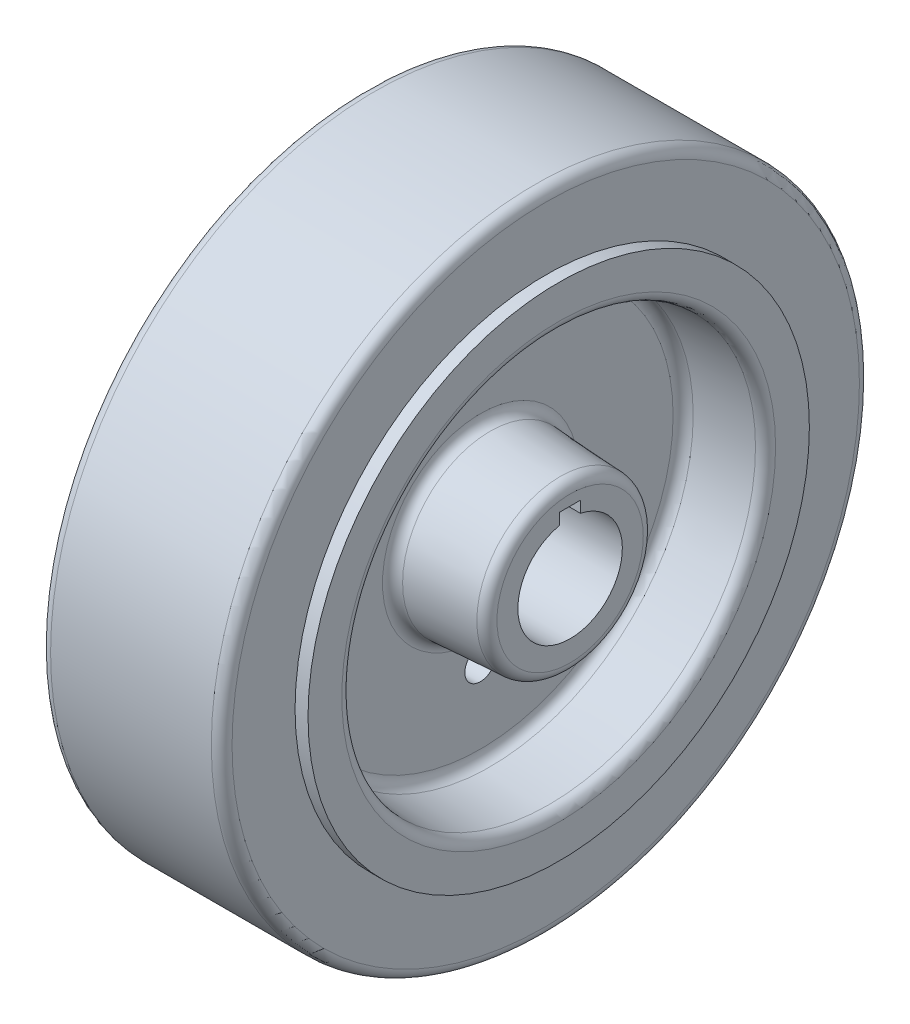
SolidWorks part; units mm, degrees
ref_plane "Front Plane" through (0, 0, 0) normal (0, 0, 1) x (1, 0, 0)
ref_plane "Top Plane" through (0, 0, 0) normal (0, 1, 0) x (1, 0, 0)
ref_plane "Right Plane" through (0, 0, 0) normal (1, 0, 0) x (0, 0, -1)
sketch "Sketch1" plane through (0, 0, 0) normal (0, 0, 1) x (1, 0, 0)
  line L0 (-17.5, -62.5) -> (17.5, -62.5)
  line L1 (-17.5, -62.5) -> (-17.5, -48.35)
  line L2 (20, -39.95) -> (4.9, -39.05)
  line L3 (4.9, -39.05) -> (4.9, -17)
  line L4 (4.9, -17) -> (22.2, -16)
  line L5 (22.2, -16) -> (22.2, -10.075)
  line L6 (0, -62.5) -> (0, 0) construction
  line L7 (0, 0) -> (22.2, 0) construction
  line L8 (22.2, -10.075) -> (-22.2, -10.075)
  line L9 (-22.2, -16) -> (-22.2, -10.075)
  line L10 (-4.9, -17) -> (-22.2, -16)
  line L11 (-4.9, -39.05) -> (-4.9, -17)
  line L12 (-20, -39.95) -> (-4.9, -39.05)
  line L13 (-17.5, -48.35) -> (-20, -48.35)
  line L14 (17.5, -62.5) -> (17.5, -48.35)
  line L15 (17.5, -48.35) -> (20, -48.35)
  line L16 (20, -48.35) -> (20, -39.95)
  line L17 (-20, -48.35) -> (-20, -39.95)
  point P12 (0, -10.075)
  dimension "D1" = 44.4
  dimension "D2" = 35
  dimension "D3" = 20.15
  dimension "D4" = 32
  dimension "D5" = 125
  dimension "D6" = 8.4
  dimension "D7" = 17.3
  dimension "D8" = 96.7
  dimension "D9" = 40
  dimension "D10" = 34
  dimension "D11" = 78.1
revolve "Revolve1" add sketch "Sketch1" angle 360 about L7
fillet "Fillet1" radius 2 10 edges at (4.9, 0, 39.05) (4.9, 0, 17) (-4.9, 0, 17) (-4.9, 0, 39.05) (22.2, 0, 16) (-22.2, 0, 16) (-17.5, 0, 62.5) (17.5, 0, 62.5) (-20, 0, 39.95) (20, 0, 39.95)
sketch "Sketch3" plane through (-22.2, 0, 0) normal (-1, 0, 0) x (0, 0, 1)
  line L0 (-2, 12.075) -> (-2, 8.075)
  line L1 (-2, 12.075) -> (2, 12.075)
  line L2 (-2, 8.075) -> (2, 8.075)
  line L3 (2, 12.075) -> (2, 8.075)
  line L4 (-2, 12.075) -> (2, 8.075) construction
  line L5 (-2, 8.075) -> (2, 12.075) construction
  line L6 (0, 0) -> (0, 10.075) construction
  circle A1 centre (0, 0) radius 10.075 construction
  point P1 (0, 10.075)
  dimension "D1" = 4
  dimension "D2" = 4
extrude "Cut-Extrude1" cut sketch "Sketch3" against normal through all
sketch "Sketch4" plane through (4.9, 0, 0) normal (1, 0, 0) x (0, 0, -1)
  circle A0 centre (0, -22.8911) radius 3
  circle A1 centre (0, -22.8911) radius 6 construction
  circle A2 centre (0, 0) radius 16.8911 construction
  dimension "D1" = 6
  dimension "D3" = 12
extrude "Cut-Extrude2" cut sketch "Sketch4" against normal through all
move or copy body "Body-Move/Copy1" [suppressed] bodies to move or copy 104
